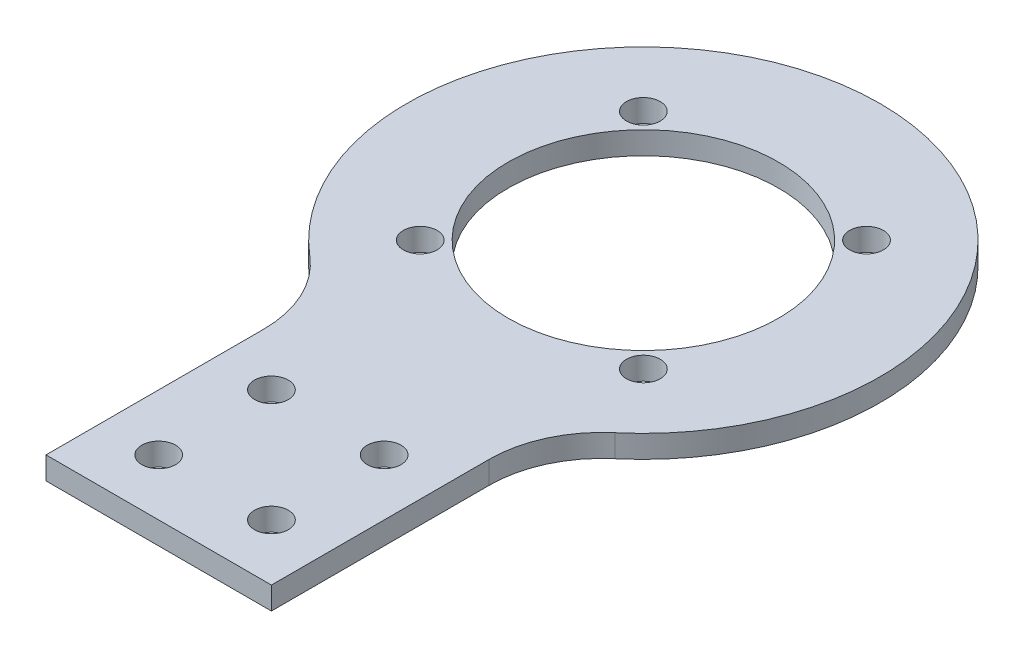
SolidWorks part; units mm, degrees
ref_plane "前视基准面" through (0, 0, 0) normal (0, 0, 1) x (1, 0, 0)
ref_plane "上视基准面" through (0, 0, 0) normal (0, 1, 0) x (1, 0, 0)
ref_plane "右视基准面" through (0, 0, 0) normal (1, 0, 0) x (0, 0, -1)
other "Configuration Table"
sketch "草图2" plane through (0, 0, 0) normal (0, 1, 0) x (1, 0, 0)
  line L5 (-23, -23) -> (23, 23) construction
  line L6 (-23, 23) -> (23, -23) construction
  circle A0 centre (0, 0) radius 21
  circle A3 centre (0, 0) radius 12
  circle A4 centre (9.8995, 9.8995) radius 1.5
  circle A5 centre (9.8995, -9.8995) radius 1.5
  circle A6 centre (-9.8995, -9.8995) radius 1.5
  circle A7 centre (-9.8995, 9.8995) radius 1.5
extrude "凸台-拉伸1" add sketch "草图2" along normal blind 2
sketch "草图4" plane through (0, 2, 0) normal (0, 1, 0) x (1, 0, 0)
  line L0 (-10, -18) -> (-10, -43)
  line L1 (-10, -18) -> (10, -18)
  line L2 (-10, -43) -> (10, -43)
  line L3 (10, -18) -> (10, -43)
  circle A0 centre (-5, -38) radius 1.5
  circle A1 centre (5, -38) radius 1.5
  circle A2 centre (-5, -28) radius 1.5
  circle A3 centre (5, -28) radius 1.5
extrude "凸台-拉伸2" add sketch "草图4" against normal blind 2
fillet "圆角1" radius 10 2 edges at (10, 1, 18.4662) (-10, 1, 18.4662)
